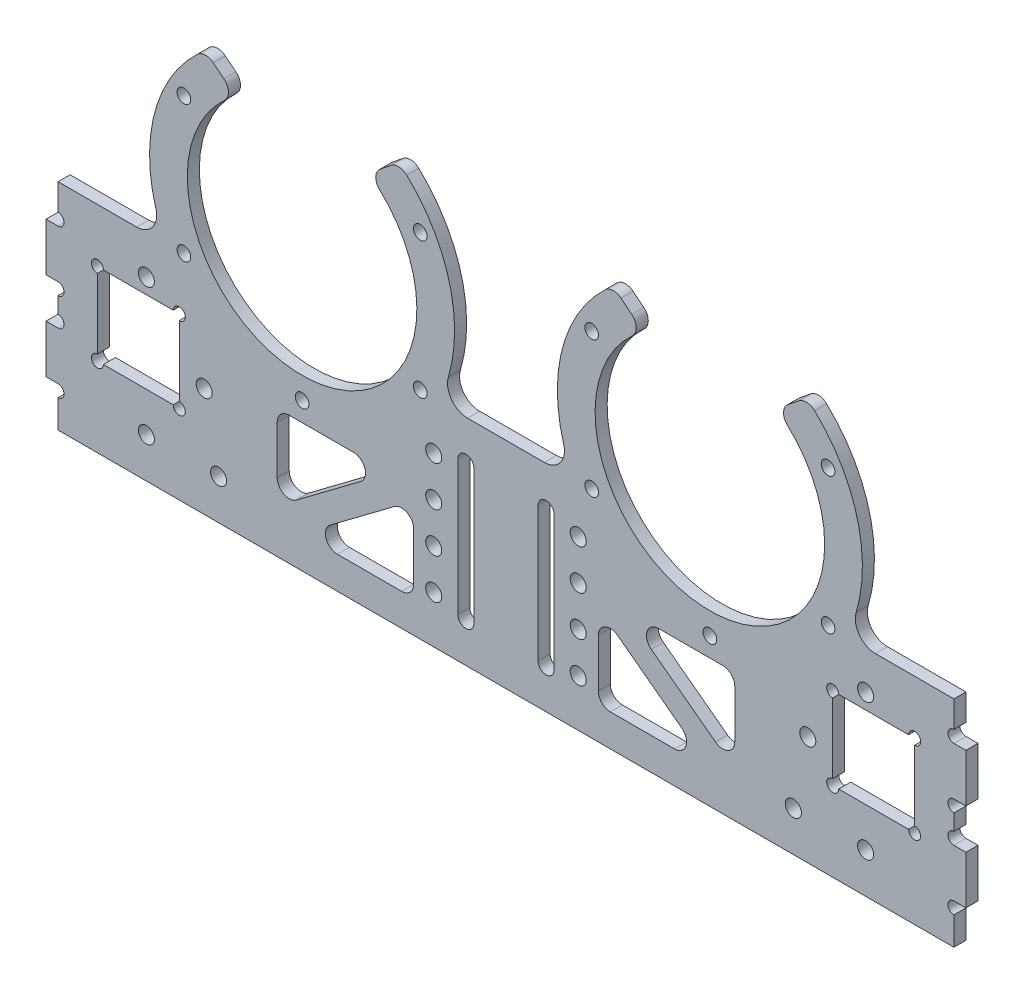
SolidWorks part; units mm, degrees
other "标注1"
sketch "草图3" plane through (101.6, -50.8, 0) normal (0.476, -0.0431, 0.8784) x (0.8786, 0.067, -0.4729)
ref_plane "前视基准面" through (0, 0, 0) normal (0, 0, 1) x (1, 0, 0)
ref_plane "上视基准面" through (0, 0, 0) normal (0, 1, 0) x (1, 0, 0)
ref_plane "右视基准面" through (0, 0, 0) normal (1, 0, 0) x (0, 0, -1)
sketch "草图1" plane through (0, 0, 0) normal (0, 0, 1) x (1, 0, 0)
  line L1 (-101.6, -60.8) -> (101.6, -60.8)
  line L2 (-101.6, -60.8) -> (-101.6, 60.8)
  line L3 (-101.6, 60.8) -> (101.6, 60.8)
  line L4 (101.6, -60.8) -> (101.6, 60.8)
  line L5 (-101.6, -60.8) -> (101.6, 60.8) construction
  line L6 (-101.6, 60.8) -> (101.6, -60.8) construction
  point P0 (0, 0)
  dimension "D1" = 121.6
  dimension "D2" = 203.2
extrude "凸台-拉伸1" add sketch "草图1" against normal blind 3
sketch "草图4" plane through (0, 0, 0) normal (0, 0, 1) x (1, 0, 0)
  line L0 (101.6, -40.8) -> (-101.6, -40.8) construction
  line L1 (101.6, -60.8) -> (101.6, 60.8) construction
  line L2 (-101.6, 60.8) -> (-101.6, -60.8) construction
  line L3 (-101.6, -60.8) -> (101.6, -60.8) construction
  line L4 (101.6, -40.8) -> (-101.6, 60.8) construction
  line L5 (-101.6, -40.8) -> (101.6, 60.8) construction
  line L6 (0, -40.8) -> (0, 60.8) construction
  line L7 (101.6, 60.8) -> (-101.6, 60.8) construction
  line L8 (0, -40.8) -> (101.6, 60.8) construction
  line L9 (0, 60.8) -> (101.6, -40.8) construction
  line L10 (0, 60.8) -> (-101.6, -40.8) construction
  line L11 (-101.6, 60.8) -> (0, -40.8) construction
  dimension "D1" = 20
sketch "草图5" plane through (0, 0, 0) normal (0, 0, 1) x (1, 0, 0)
  line L0 (0, 60.8) -> (-101.6, -40.8) construction
  line L1 (0, -40.8) -> (101.6, 60.8) construction
  line L2 (-50.8, 10) -> (-50.8, 60.8) construction
  line L4 (101.6, 60.8) -> (-101.6, 60.8) construction
  line L6 (50.8, 10) -> (50.8, 60.8) construction
  line L7 (-50.8, 10) -> (-21.3551, 27) construction
  line L8 (80.2449, 27) -> (50.8, 10) construction
  circle A0 centre (-50.8, 10) radius 20.75
  circle A1 centre (50.8, 10) radius 20.75
  circle A2 centre (-50.8, 10) radius 34 construction
  circle A3 centre (50.8, 10) radius 34 construction
  circle A4 centre (-50.8, 44) radius 1.7
  circle A5 centre (-21.3551, 27) radius 1.7
  circle A6 centre (-21.3551, -7) radius 1.7
  circle A7 centre (-50.8, -24) radius 1.7
  circle A8 centre (-80.2449, -7) radius 1.7
  circle A9 centre (-80.2449, 27) radius 1.7
  circle A10 centre (50.8, 44) radius 1.7
  circle A11 centre (80.2449, 27) radius 1.7
  circle A32 centre (80.2449, -7) radius 1.7
  circle A57 centre (50.8, -24) radius 1.7
  circle A58 centre (21.3551, -7) radius 1.7
  circle A59 centre (21.3551, 27) radius 1.7
  point P29 (-50.8, 10)
  point P41 (50.8, 10)
  dimension "D1" = 41.5
  dimension "D2" = 41.5
  dimension "D3" = 68
  dimension "D4" = 68
  dimension "D5" = 3.4
  dimension "D7" = 3.4
  dimension "D6" = 6
  dimension "D8" = 6
  dimension "D9" = 60
  dimension "D10" = 34
  dimension "D11" = 60
  dimension "D12" = 34
extrude "切除-拉伸1" cut sketch "草图5" against normal up to next
sketch "草图6" plane through (0, 0, -3) normal (0, 0, -1) x (-1, 0, 0)
  line L0 (-101.6, -60.8) -> (-101.6, 60.8) construction
  line L2 (-101.6, -20.8) -> (101.6, -20.8)
  line L4 (0, -20.8) -> (0, 60.8) construction
  line L5 (-101.6, 60.8) -> (101.6, 60.8) construction
  line L6 (0, 60.8) -> (-101.6, -20.8)
  line L7 (101.6, -60.8) -> (-101.6, -60.8) construction
  line L8 (-101.6, -7.2102) -> (101.6, -7.2102)
  line L9 (0, 60.8) -> (101.6, -20.8)
  line L10 (-101.6, 60.8) -> (0, -20.8)
  line L11 (0, -20.8) -> (101.6, 60.8)
  line L12 (-101.6, 60.8) -> (101.6, 60.8)
  line L13 (101.6, 60.8) -> (101.6, -60.8) construction
  line L14 (-101.6, 60.8) -> (-101.6, -20.8)
  line L15 (101.6, 60.8) -> (101.6, -20.8)
  circle A0 centre (-50.8, 10) radius 20.75 construction
  circle A1 centre (50.8, 10) radius 20.75 construction
  arc A2 (26.6851, 39.3679) -> (74.9149, 39.3679) centre (50.8, 10) ccw
  arc A3 (-74.9149, 39.3679) -> (-26.6851, 39.3679) centre (-50.8, 10) ccw
  arc A6 (-87.2358, -0.7904) -> (-92.03, -7.2102) centre (-92.03, -2.2102) cw
  arc A7 (-14.3642, -0.7904) -> (-9.57, -7.2102) centre (-9.57, -2.2102) ccw
  arc A8 (14.3642, -0.7904) -> (9.57, -7.2102) centre (9.57, -2.2102) cw
  arc A9 (87.2358, -0.7904) -> (92.03, -7.2102) centre (92.03, -2.2102) ccw
  circle A14 centre (50.8, 10) radius 28.6
  circle A15 centre (-50.8, 10) radius 28.6
  point P21 (-84.6793, -7.2102)
  point P23 (84.6793, -7.2102)
  dimension "D2" = 76
  dimension "D3" = 76
  dimension "D4" = 5
  dimension "D5" = 5
  dimension "D6" = 5
  dimension "D7" = 5
  dimension "D8" = 57.2
  dimension "D9" = 57.2
  dimension "D1" = 40
extrude "切除-拉伸2" cut sketch "草图6" against normal up to next
sketch "草图7" plane through (101.6, 0, 0) normal (1, 0, 0) x (0, 0, -1)
  line L4 (3, -7.2102) -> (0, -7.2102)
  line L5 (0, -7.2102) -> (0, -60.8)
  line L6 (0, -60.8) -> (3, -60.8)
  line L7 (3, -60.8) -> (3, -7.2102)
  line L9 (0, -7.2102) -> (0, -60.8)
  line L10 (0, -60.8) -> (3, -60.8)
  line L11 (3, -60.8) -> (3, -7.2102)
  line L13 (3, -7.2102) -> (0, -7.2102)
  dimension "D1" = 0
extrude "凸台-拉伸2" add sketch "草图7" along normal blind 13
sketch "草图9" plane through (-101.6, 0, 0) normal (-1, 0, 0) x (0, 0, 1)
  line L4 (0, -7.2102) -> (-3, -7.2102)
  line L5 (-3, -7.2102) -> (-3, -60.8)
  line L6 (-3, -60.8) -> (0, -60.8)
  line L7 (0, -60.8) -> (0, -7.2102)
  line L9 (-3, -7.2102) -> (-3, -60.8)
  line L10 (-3, -60.8) -> (0, -60.8)
  line L11 (0, -60.8) -> (0, -7.2102)
  line L13 (0, -7.2102) -> (-3, -7.2102)
  dimension "D1" = 0
extrude "凸台-拉伸3" add sketch "草图9" along normal blind 13
sketch "草图12" plane through (0, 0, -3) normal (0, 0, -1) x (-1, 0, 0)
  line L1 (-114.6, -60.8) -> (-114.6, -7.2102) construction
  line L2 (92.03, -7.2102) -> (114.6, -7.2102) construction
  line L3 (114.6, -7.2102) -> (114.6, -60.8) construction
  line L16 (-101.8, -20.6) -> (-101.8, -41)
  line L17 (-101.8, -41) -> (-81.4, -41)
  line L18 (-81.4, -41) -> (-81.4, -20.6)
  line L19 (-81.4, -20.6) -> (-101.8, -20.6)
  line L20 (81.4, -20.6) -> (81.4, -41)
  line L21 (81.4, -41) -> (101.8, -41)
  line L22 (101.8, -41) -> (101.8, -20.6)
  line L23 (101.8, -20.6) -> (81.4, -20.6)
  line L24 (-114.6, -7.2102) -> (-92.03, -7.2102) construction
  arc A0 (-100.3, -20.6) -> (-101.8, -22.1) centre (-101.8, -20.6) ccw
  arc A1 (-81.4, -22.1) -> (-82.9, -20.6) centre (-81.4, -20.6) ccw
  arc A2 (-82.9, -41) -> (-81.4, -39.5) centre (-81.4, -41) ccw
  arc A3 (-101.8, -39.5) -> (-100.3, -41) centre (-101.8, -41) ccw
  arc A4 (82.9, -20.6) -> (81.4, -22.1) centre (81.4, -20.6) ccw
  arc A5 (81.4, -39.5) -> (82.9, -41) centre (81.4, -41) ccw
  arc A6 (100.3, -41) -> (101.8, -39.5) centre (101.8, -41) ccw
  arc A7 (101.8, -22.1) -> (100.3, -20.6) centre (101.8, -20.6) ccw
  dimension "D7" = 3
  dimension "D8" = 3
  dimension "D9" = 3
  dimension "D10" = 3
  dimension "D11" = 3
  dimension "D12" = 3
  dimension "D13" = 3
  dimension "D14" = 3
  dimension "D1" = 12.8
  dimension "D2" = 13.3898
  dimension "D3" = 20.4
  dimension "D4" = 13.3898
  dimension "D5" = 12.8
  dimension "D6" = 20.4
extrude "切除-拉伸6" cut sketch "草图12" against normal through all contours L18 L19 L16 L17 | L19 A0 L16 | L16 A3 L17 | L17 A2 L18 | L18 A1 L19 | L23 A4 L20 | L22 A7 L23 | L21 A6 L22 | L22 L23 L20 L21 | L20 A5 L21
sketch "草图13" plane through (0, 0, -3) normal (0, 0, -1) x (-1, 0, 0)
  circle A2 centre (89.6, -50.8) radius 2
  circle A3 centre (-89.6, -50.8) radius 2
  circle A6 centre (71.6, -50.8) radius 2
  circle A7 centre (75.1892, -33.6216) radius 2
  circle A8 centre (89.6, -16.8) radius 2
  circle A9 centre (-71.6, -50.8) radius 2
  circle A10 centre (-89.6, -16.8) radius 2
  circle A11 centre (-75.1892, -33.6216) radius 2
extrude "切除-拉伸7" cut sketch "草图13" against normal through all
sketch "草图14" plane through (0, 0, 0) normal (0, 0, 1) x (1, 0, 0)
  line L0 (0, -7.2102) -> (0, -60.8) construction
  line L1 (-9.57, -7.2102) -> (9.57, -7.2102) construction
  line L2 (-114.6, -60.8) -> (114.6, -60.8) construction
  line L3 (-10, -17.2102) -> (-10, -50.8) construction
  line L4 (-8, -17.2102) -> (-8, -50.8)
  line L5 (-12, -17.2102) -> (-12, -50.8)
  line L6 (0, -34.0051) -> (20.1146, -34.0051) construction
  line L7 (10, -17.2102) -> (10, -50.8) construction
  line L8 (8, -17.2102) -> (8, -50.8)
  line L9 (12, -17.2102) -> (12, -50.8)
  line L16 (23, -52.8) -> (51, -52.8)
  line L28 (20, -55.8) -> (60, -55.8) construction
  line L29 (20, -55.8) -> (20, -25.8) construction
  line L30 (20, -25.8) -> (60, -25.8) construction
  line L31 (60, -55.8) -> (60, -25.8) construction
  line L32 (20, -55.8) -> (60, -25.8) construction
  line L33 (20, -25.8) -> (60, -55.8) construction
  line L34 (23, -31.8) -> (51, -52.8)
  line L35 (23, -52.8) -> (23, -31.8)
  line L36 (57, -49.8) -> (57, -28.8)
  line L37 (29, -28.8) -> (57, -28.8)
  line L38 (29, -28.8) -> (57, -49.8)
  line L39 (-23, -52.8) -> (-23, -31.8)
  line L40 (-23, -31.8) -> (-51, -52.8)
  line L41 (-23, -52.8) -> (-51, -52.8)
  line L42 (-29, -28.8) -> (-57, -49.8)
  line L43 (-29, -28.8) -> (-57, -28.8)
  line L44 (-57, -49.8) -> (-57, -28.8)
  arc A0 (-8, -17.2102) -> (-12, -17.2102) centre (-10, -17.2102) ccw
  arc A1 (-12, -50.8) -> (-8, -50.8) centre (-10, -50.8) ccw
  arc A2 (8, -17.2102) -> (12, -17.2102) centre (10, -17.2102) cw
  arc A3 (12, -50.8) -> (8, -50.8) centre (10, -50.8) cw
  circle A4 centre (18, -19.0051) radius 2
  circle A5 centre (18, -29.0051) radius 2
  circle A6 centre (18, -39.0051) radius 2
  circle A7 centre (18, -49.0051) radius 2
  circle A8 centre (-18, -49.0051) radius 2
  circle A9 centre (-18, -39.0051) radius 2
  circle A10 centre (-18, -29.0051) radius 2
  circle A11 centre (-18, -19.0051) radius 2
  point P8 (-10, -34.0051)
  point P15 (0, -34.0051)
  point P19 (10, -34.0051)
  point P24 (40, -40.8)
  dimension "D2" = 2
  dimension "D10" = 4
  dimension "D11" = 18
  dimension "D1" = 10
  dimension "D3" = 10
  dimension "D4" = 20
  dimension "D5" = 40
  dimension "D6" = 40
  dimension "D7" = 30
  dimension "D12" = 15
  dimension "D8" = 3
  dimension "D9" = 3
  dimension "D13" = 4
extrude "切除-拉伸8" cut sketch "草图14" against normal through all
fillet "圆角1" radius 3 20 edges at (23, -52.8, -1.5) (51, -52.8, -1.5) (23, -31.8, -1.5) (29, -28.8, -1.5) (57, -28.8, -1.5) (57, -49.8, -1.5) (-23, -52.8, -1.5) (-23, -31.8, -1.5) (-51, -52.8, -1.5) (-57, -49.8, -1.5) (-29, -28.8, -1.5) (-57, -28.8, -1.5) (67.3717, 33.3096, -1.5) (74.9149, 39.3679, -1.5) (34.2283, 33.3096, -1.5) (26.6851, 39.3679, -1.5) (-34.2283, 33.3096, -1.5) (-26.6851, 39.3679, -1.5) (-74.9149, 39.3679, -1.5) (-67.3717, 33.3096, -1.5)
sketch "草图15" plane through (0, 0, 0) normal (0, 0, 1) x (1, 0, 0)
  line L0 (-114.6, -60.8) -> (-114.6, -7.2102) construction
  line L5 (0, -1.65) -> (0, 1.65) construction
  line L6 (-114.6, -38.8) -> (-111.6, -38.8)
  line L7 (-114.6, -38.8) -> (-114.6, -28.8)
  line L8 (-114.6, -28.8) -> (-111.6, -28.8)
  line L9 (-111.6, -35.8) -> (-111.6, -31.8)
  line L10 (-114.6, -60.8) -> (-111.6, -60.8)
  line L11 (-114.6, -60.8) -> (-114.6, -50.8)
  line L12 (-114.6, -50.8) -> (-111.6, -50.8)
  line L13 (-111.6, -60.8) -> (-111.6, -53.8)
  line L14 (-114.6, -7.2102) -> (-111.6, -7.2102)
  line L15 (-114.6, -7.2102) -> (-114.6, -16.8)
  line L16 (-114.6, -16.8) -> (-111.6, -16.8)
  line L17 (-111.6, -7.2102) -> (-111.6, -13.8)
  line L18 (111.6, -60.8) -> (111.6, -53.8)
  line L19 (114.6, -60.8) -> (111.6, -60.8)
  line L20 (114.6, -60.8) -> (114.6, -50.8)
  line L21 (114.6, -50.8) -> (111.6, -50.8)
  line L22 (111.6, -35.8) -> (111.6, -31.8)
  line L23 (114.6, -38.8) -> (111.6, -38.8)
  line L24 (114.6, -38.8) -> (114.6, -28.8)
  line L25 (114.6, -28.8) -> (111.6, -28.8)
  line L26 (114.6, -16.8) -> (111.6, -16.8)
  line L27 (114.6, -7.2102) -> (114.6, -16.8)
  line L28 (114.6, -7.2102) -> (111.6, -7.2102)
  line L29 (111.6, -7.2102) -> (111.6, -13.8)
  arc A0 (-111.6, -16.8) -> (-111.6, -13.8) centre (-111.6, -15.3) ccw
  arc A1 (-111.6, -31.8) -> (-111.6, -28.8) centre (-111.6, -30.3) ccw
  arc A2 (-111.6, -38.8) -> (-111.6, -35.8) centre (-111.6, -37.3) ccw
  arc A3 (-111.6, -53.8) -> (-111.6, -50.8) centre (-111.6, -52.3) ccw
  arc A4 (111.6, -53.8) -> (111.6, -50.8) centre (111.6, -52.3) cw
  arc A5 (111.6, -38.8) -> (111.6, -35.8) centre (111.6, -37.3) cw
  arc A6 (111.6, -31.8) -> (111.6, -28.8) centre (111.6, -30.3) cw
  arc A7 (111.6, -16.8) -> (111.6, -13.8) centre (111.6, -15.3) cw
  dimension "D6" = 3
  dimension "D7" = 3
  dimension "D8" = 3
  dimension "D9" = 3
  dimension "D1" = 10
  dimension "D2" = 3
  dimension "D3" = 12
  dimension "D4" = 10
  dimension "D5" = 12
extrude "切除-拉伸9" cut sketch "草图15" against normal through all
